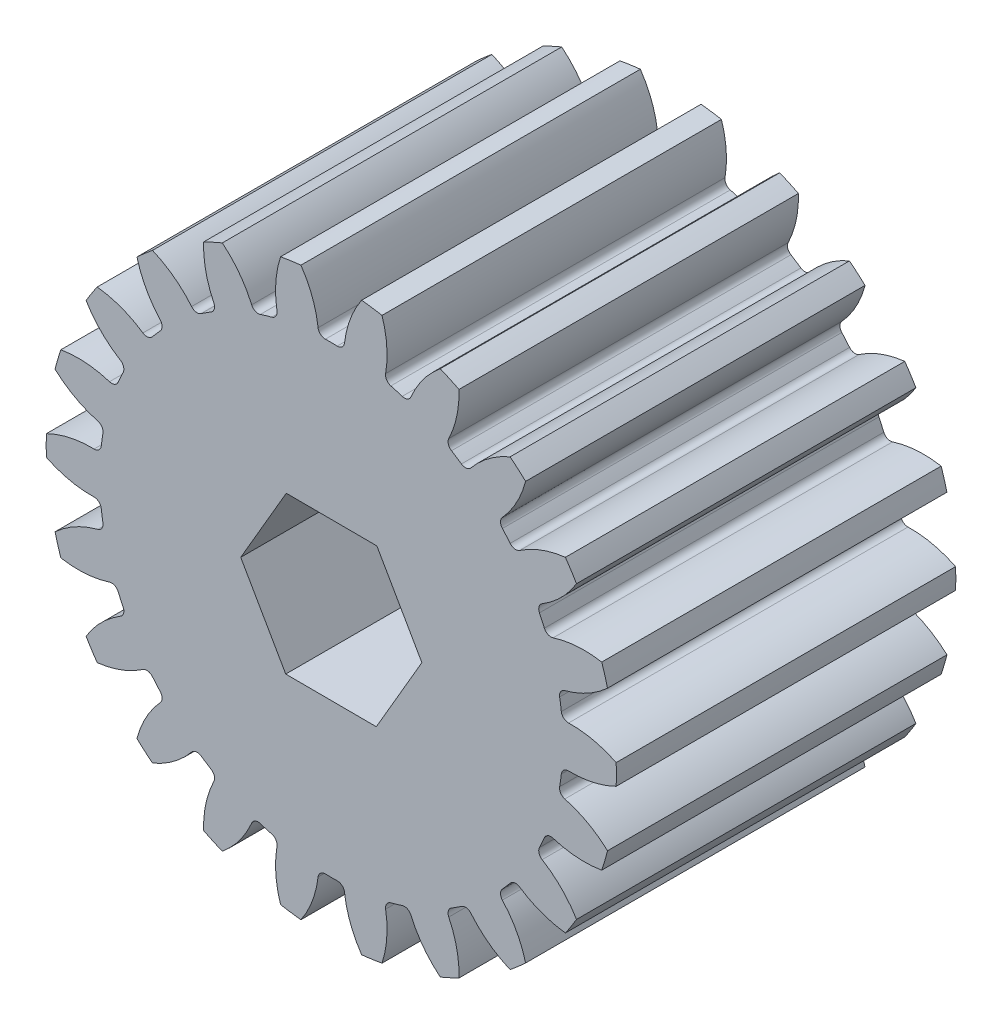
SolidWorks part; units mm, degrees
material "ABS"
ref_plane "Front Plane" through (0, 0, 0) normal (0, 0, 1) x (1, 0, 0)
ref_plane "Top Plane" through (0, 0, 0) normal (0, 1, 0) x (1, 0, 0)
ref_plane "Right Plane" through (0, 0, 0) normal (1, 0, 0) x (0, 0, -1)
sketch "Sketch1" plane through (0, 0, 0) normal (0, 0, 1) x (1, 0, 0)
  circle A0 centre (0, 0) radius 22
  circle A2 centre (0, 0) radius 24
  circle A3 centre (0, 0) radius 19.5
  dimension "D1" = 44
  dimension "D2" = 48
  dimension "D3" = 4.5
extrude "Boss-Extrude1" add sketch "Sketch1" along normal blind 25.4 and the other way blind 3.175 contours A2
sketch "Sketch3" plane through (0, 0, -3.175) normal (0, 0, -1) x (-1, 0, 0)
  line L0 (0, 0) -> (0, 24) construction
  line L1 (-1.5695, 21.9439) -> (1.5695, 21.9439) construction
  line L2 (0, 0) -> (-1.0635, 19.471) construction
  line L3 (0, 17.6319) -> (-2.6312, 24.8611) construction
  line L4 (0, 0) -> (3.4156, 23.7557) construction
  line L5 (1.5695, 21.9439) -> (4.6764, 21.4972) construction
  circle A0 centre (0, 0) radius 24 construction
  arc A1 (-3.2834, 24.7834) -> (-1.0635, 19.471) centre (-9.6529, 19.0018) cw
  arc A2 (3.2834, 24.7834) -> (1.0635, 19.471) centre (9.6529, 19.0018) ccw
  circle A3 centre (0, 0) radius 19.5 construction
  arc A4 (1.0635, 19.471) -> (-1.0635, 19.471) centre (0, 0) ccw
  arc A5 (3.2834, 24.7834) -> (-3.2834, 24.7834) centre (0, 0) ccw
  circle A6 centre (0, 0) radius 22 construction
  circle A8 centre (0, 0) radius 22 construction
  dimension "D1" = 1
  dimension "D2" = 20
  dimension "D3" = 8.182
extrude "Cut-Extrude2" cut sketch "Sketch3" against normal through all
fillet "Fillet2" radius 0.6 2 edges at (-1.0635, 19.471, 11.1125) (1.0635, 19.471, 11.1125)
pattern_circular "CirPattern2" count 22 over 360 about axis through (0, 0, 0) along (0, 0, 1) of "Cut-Extrude2", "Fillet2"
sketch "Sketch4" plane through (0, 0, 25.4) normal (0, 0, 1) x (1, 0, 0)
  line L1 (3.8362, 6.5904) -> (-3.7894, 6.6175)
  line L2 (-3.7894, 6.6175) -> (-7.6256, 0.027)
  line L3 (-7.6256, 0.027) -> (-3.8362, -6.5904)
  line L4 (-3.8362, -6.5904) -> (3.7894, -6.6175)
  line L5 (3.7894, -6.6175) -> (7.6256, -0.027)
  line L6 (7.6256, -0.027) -> (3.8362, 6.5904)
  circle A0 centre (0, 0) radius 6.604 construction
  dimension "D1" = 13.208
extrude "Cut-Extrude3" cut sketch "Sketch4" against normal through all
sketch "Diametral Pitch (for mating)" plane through (0, 0, 25.4) normal (0, 0, 1) x (1, 0, 0)
  circle A0 centre (0, 0) radius 22
  dimension "D1" = 44
equation "\"Module\"= 2mm"
equation "\"Number of Teeth\"= 22"
equation "\"D1@Sketch1\"=\"Module\"*\"Number of Teeth\""
equation "\"D2@Sketch1\"=(\"Number of Teeth\"+2) * \"Module\""
equation "\"D3@Sketch3\"=180 /\"Number of Teeth\" "
equation "\"D1@Fillet2\"=.3 * \"Module\""
equation "\"D1@CirPattern2\"=\"Number of Teeth\""
equation "\"D3@Sketch1\"=\"Module\"*if( \"Module\"=>1.25,2.25,2.4)"
equation "\"D1@Diametral Pitch (for mating)\" = \"Module\" * \"Number of Teeth\""
